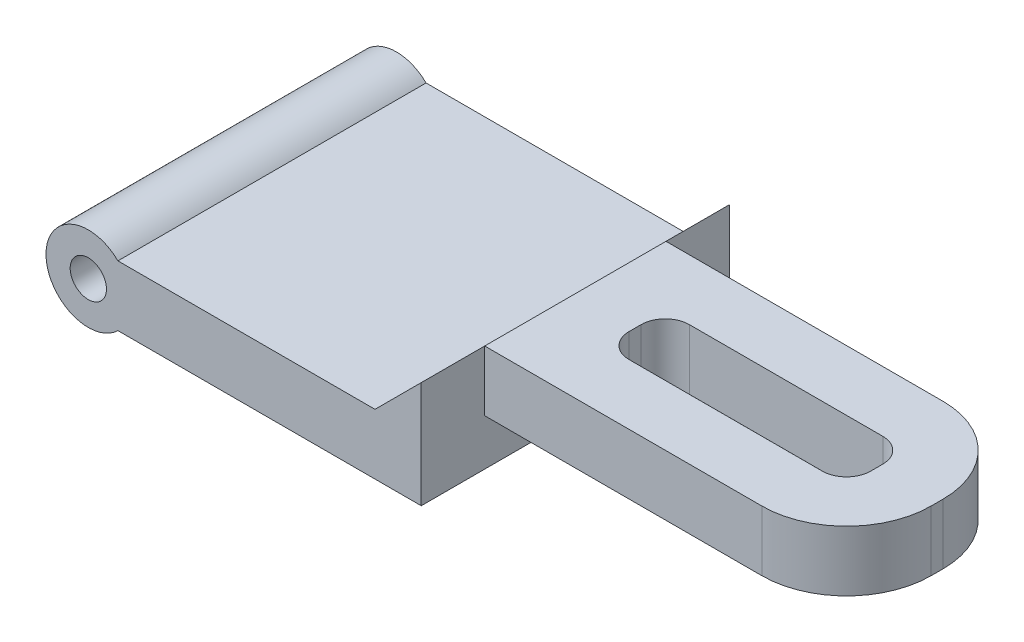
SolidWorks part; units mm, degrees
ref_plane "Alzado" through (0, 0, 0) normal (0, 0, 1) x (1, 0, 0)
ref_plane "Planta" through (0, 0, 0) normal (0, 1, 0) x (1, 0, 0)
ref_plane "Vista lateral" through (0, 0, 0) normal (1, 0, 0) x (0, 0, -1)
sketch "Croquis1" plane through (0, 0, 0) normal (0, 1, 0) x (1, 0, 0)
  line L1 (0, 0) -> (30, 0)
  line L2 (0, 0) -> (0, 25.5)
  line L3 (0, 25.5) -> (30, 25.5)
  line L4 (30, 0) -> (30, 25.5)
  dimension "D1" = 25.5
  dimension "D2" = 30
extrude "Saliente-Extruir1" add sketch "Croquis1" along normal blind 5 contours L1 L4 L3 L2
sketch "Croquis2" plane through (0, 0, 0) normal (0, 0, 1) x (1, 0, 0)
  line L0 (26.1735, 5) -> (30, 8.8265)
  line L1 (0, 5) -> (30, 5) construction
  line L2 (30, 8.8265) -> (60, 8.8265)
  line L3 (60, 8.8265) -> (60, 3.8298)
  line L4 (60, 3.8298) -> (30, 3.8298)
  line L5 (30, 5) -> (30, 0) construction
  line L6 (30, 3.8298) -> (30, 5)
  line L7 (30, 5) -> (26.1735, 5)
  dimension "D1" = 4.9967
  dimension "D2" = 3.8265
  dimension "D3" = 45
  dimension "D4" = 30
  dimension "D5" = 1.1702
extrude "Saliente-Extruir2" add sketch "Croquis2" against normal up to vertex (25.5 mm away)
sketch "Croquis3" plane through (0, 0, 0) normal (0, 0, 1) x (1, 0, 0)
  circle A0 centre (2.4495, 2.5) radius 3.5
  dimension "D1" = 7
extrude "Saliente-Extruir3" add sketch "Croquis3" against normal up to vertex (25.5 mm away)
sketch "Croquis4" plane through (0, 0, 0) normal (0, 0, 1) x (1, 0, 0)
  circle A0 centre (2.4495, 2.5) radius 1.5
  dimension "D1" = 3
extrude "Cortar-Extruir1" cut sketch "Croquis4" against normal blind 31
sketch "Croquis5" plane through (0, 3.8298, 0) normal (0, -1, 0) x (1, 0, 0)
  line L0 (60, -12.75) -> (30, -12.75) construction
  line L1 (60, -25.5) -> (60, 0) construction
  line L2 (30, 0) -> (30, -25.5) construction
  line L4 (52.9386, -10.25) -> (36.9386, -10.25)
  line L5 (54.9386, -12.25) -> (54.9386, -13.25)
  line L6 (52.9386, -15.25) -> (36.9386, -15.25)
  line L7 (34.9386, -12.25) -> (34.9386, -13.25)
  arc A4 (34.9386, -13.25) -> (36.9386, -15.25) centre (36.9386, -13.25) ccw
  arc A5 (34.9386, -12.25) -> (36.9386, -10.25) centre (36.9386, -12.25) cw
  arc A6 (52.9386, -15.25) -> (54.9386, -13.25) centre (52.9386, -13.25) ccw
  arc A7 (54.9386, -12.25) -> (52.9386, -10.25) centre (52.9386, -12.25) ccw
  point P10 (54.9386, -12.75)
  point P19 (34.9386, -12.75)
  dimension "D1" = 2
  dimension "D2" = 5
  dimension "D3" = 20
  dimension "D4" = 4.9386
extrude "Cortar-Extruir2" cut sketch "Croquis5" against normal blind 31
sketch "Croquis6" plane through (0, 3.8298, 0) normal (0, -1, 0) x (1, 0, 0)
  line L10 (36.9386, -5.25) -> (30, -5.25)
  line L11 (30, 0) -> (30, -25.5) construction
  line L12 (30, -5.25) -> (30, 0)
  line L13 (59.9386, -13.25) -> (59.9386, -12.25)
  line L14 (36.9386, -20.25) -> (52.9386, -20.25)
  line L15 (52.9386, -5.25) -> (36.9386, -5.25)
  line L16 (59.9386, -13.25) -> (59.9386, -12.25)
  line L17 (36.9386, -20.25) -> (52.9386, -20.25)
  line L18 (52.9386, -5.25) -> (36.9386, -5.25)
  line L19 (30, 0) -> (60, 0)
  line L21 (60, -25.5) -> (60, 0) construction
  line L22 (60, -25.5) -> (60, 0)
  line L23 (60, -25.5) -> (30, -25.5)
  line L24 (30, -25.5) -> (30, -20.25)
  line L25 (30, -25.5) -> (30, 0) construction
  line L26 (30, -20.25) -> (36.9386, -20.25)
  arc A7 (52.9386, -20.25) -> (59.9386, -13.25) centre (52.9386, -13.25) ccw
  arc A8 (59.9386, -12.25) -> (52.9386, -5.25) centre (52.9386, -12.25) ccw
  arc A9 (52.9386, -20.25) -> (59.9386, -13.25) centre (52.9386, -13.25) ccw
  arc A10 (59.9386, -12.25) -> (52.9386, -5.25) centre (52.9386, -12.25) ccw
  dimension "D1" = 5
extrude "Cortar-Extruir3" cut sketch "Croquis6" against normal blind 12
